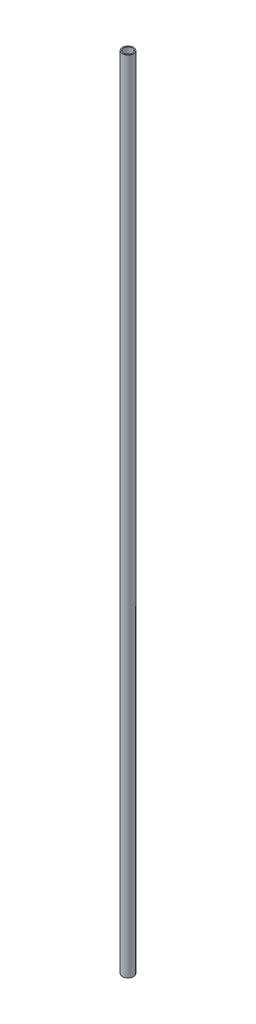
SolidWorks part; units mm, degrees
material "6061-T6 (SS)"
ref_plane "Front Plane" through (0, 0, 0) normal (0, 0, 1) x (1, 0, 0)
ref_plane "Top Plane" through (0, 0, 0) normal (0, 1, 0) x (1, 0, 0)
ref_plane "Right Plane" through (0, 0, 0) normal (1, 0, 0) x (0, 0, -1)
sketch "Sketch1" plane through (0, 0, 0) normal (0, 1, 0) x (1, 0, 0)
  circle A0 centre (0, 0) radius 6.35
  circle A1 centre (0, 0) radius 5.1054
  dimension "D1" = 12.7
  dimension "D2" = 10.2108
extrude "Boss-Extrude1" add sketch "Sketch1" along normal blind 914.4
ref_point "Point2"
